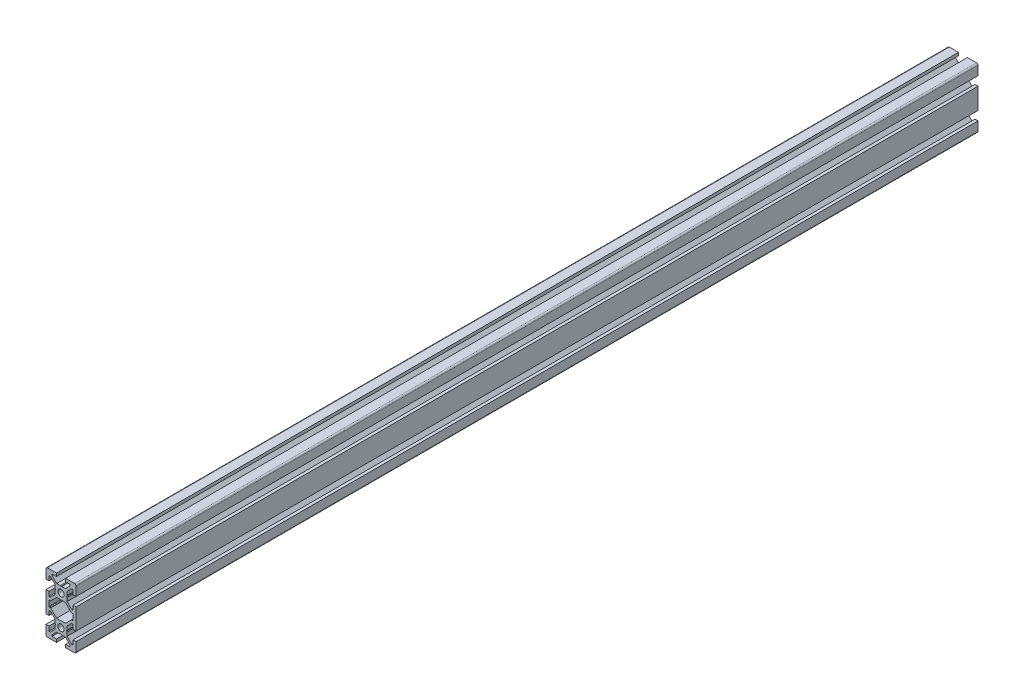
SolidWorks part; units mm, degrees
ref_plane "Front Plane" through (0, 0, 0) normal (0, 0, 1) x (1, 0, 0)
ref_plane "Top Plane" through (0, 0, 0) normal (0, 1, 0) x (1, 0, 0)
ref_plane "Right Plane" through (0, 0, 0) normal (1, 0, 0) x (0, 0, -1)
sketch "Sketch1" plane through (0, 0, 0) normal (0, 0, 1) x (1, 0, 0)
  line L0 (-8, -16) -> (-8, -13)
  line L1 (-8, -13) -> (-10, -13)
  line L2 (-10, -13) -> (-10, -19)
  line L3 (-9, -20) -> (-3, -20)
  line L4 (-3, -20) -> (-3, -18)
  line L5 (-3, -18) -> (-6, -18)
  line L6 (-6, -18) -> (-6, -17.0607)
  line L7 (-6, -17.0607) -> (-2.9393, -14)
  line L8 (-2.9393, -14) -> (-0.5196, -14)
  line L9 (-0.5196, -14) -> (0, -13.7)
  line L10 (0, -13.7) -> (0.5196, -14)
  line L11 (0.5196, -14) -> (2.9393, -14)
  line L12 (2.9393, -14) -> (6, -17.0607)
  line L13 (6, -17.0607) -> (6, -18)
  line L14 (6, -18) -> (3, -18)
  line L15 (3, -18) -> (3, -20)
  line L16 (3, -20) -> (9, -20)
  line L17 (10, -19) -> (10, -13)
  line L18 (10, -13) -> (8, -13)
  line L19 (8, -13) -> (8, -16)
  line L20 (8, -16) -> (7.0607, -16)
  line L21 (7.0607, -16) -> (4, -12.9393)
  line L22 (4, -12.9393) -> (4, -10.5196)
  line L23 (4, -10.5196) -> (3.7, -10)
  line L24 (3.7, -10) -> (4, -9.4804)
  line L25 (4, -9.4804) -> (4, -7.0607)
  line L26 (4, -7.0607) -> (7.0607, -4)
  line L27 (7.0607, -4) -> (8, -4)
  line L28 (8, -4) -> (8, -7)
  line L29 (8, -7) -> (10, -7)
  line L30 (10, -7) -> (10, 7)
  line L31 (10, 7) -> (8, 7)
  line L32 (8, 7) -> (8, 4)
  line L33 (8, 4) -> (7.0607, 4)
  line L34 (7.0607, 4) -> (4, 7.0607)
  line L35 (4, 7.0607) -> (4, 9.4804)
  line L36 (4, 9.4804) -> (3.7, 10)
  line L37 (3.7, 10) -> (4, 10.5196)
  line L38 (4, 10.5196) -> (4, 12.9393)
  line L39 (4, 12.9393) -> (7.0607, 16)
  line L40 (7.0607, 16) -> (8, 16)
  line L41 (8, 16) -> (8, 13)
  line L42 (8, 13) -> (10, 13)
  line L43 (10, 13) -> (10, 19)
  line L44 (9, 20) -> (3, 20)
  line L45 (3, 20) -> (3, 18)
  line L46 (3, 18) -> (6, 18)
  line L47 (6, 18) -> (6, 17.0607)
  line L48 (6, 17.0607) -> (2.9393, 14)
  line L49 (2.9393, 14) -> (0.5196, 14)
  line L50 (0.5196, 14) -> (0, 13.7)
  line L51 (0, 13.7) -> (-0.5196, 14)
  line L52 (-0.5196, 14) -> (-2.9393, 14)
  line L53 (-2.9393, 14) -> (-6, 17.0607)
  line L54 (-6, 17.0607) -> (-6, 18)
  line L55 (-6, 18) -> (-3, 18)
  line L56 (-3, 18) -> (-3, 20)
  line L57 (-3, 20) -> (-9, 20)
  line L58 (-10, 19) -> (-10, 13)
  line L59 (-10, 13) -> (-8, 13)
  line L60 (-8, 13) -> (-8, 16)
  line L61 (-8, 16) -> (-7.0607, 16)
  line L62 (-7.0607, 16) -> (-4, 12.9393)
  line L63 (-4, 12.9393) -> (-4, 10.5196)
  line L64 (-4, 10.5196) -> (-3.7, 10)
  line L65 (-3.7, 10) -> (-4, 9.4804)
  line L66 (-4, 9.4804) -> (-4, 7.0607)
  line L67 (-4, 7.0607) -> (-7.0607, 4)
  line L68 (-7.0607, 4) -> (-8, 4)
  line L69 (-8, 4) -> (-8, 7)
  line L70 (-8, 7) -> (-10, 7)
  line L71 (-10, 7) -> (-10, -7)
  line L72 (-10, -7) -> (-8, -7)
  line L73 (-8, -7) -> (-8, -4)
  line L74 (-8, -4) -> (-7.0607, -4)
  line L75 (-7.0607, -4) -> (-4, -7.0607)
  line L76 (-4, -7.0607) -> (-4, -9.4804)
  line L77 (-4, -9.4804) -> (-3.7, -10)
  line L78 (-3.7, -10) -> (-4, -10.5196)
  line L79 (-4, -10.5196) -> (-4, -12.9393)
  line L80 (-4, -12.9393) -> (-7.0607, -16)
  line L81 (-7.0607, -16) -> (-8, -16)
  line L82 (-7.0636, -2) -> (-7.7, -2)
  line L83 (-8, -1.7) -> (-8, 1.7)
  line L84 (-7.7, 2) -> (-7.0636, 2)
  line L85 (-6.8515, 2.0879) -> (-2.9393, 6)
  line L86 (-2.9393, 6) -> (2.9393, 6)
  line L87 (2.9393, 6) -> (6.8515, 2.0879)
  line L88 (7.0636, 2) -> (7.7, 2)
  line L89 (8, 1.7) -> (8, -1.7)
  line L90 (7.7, -2) -> (7.0636, -2)
  line L91 (6.8515, -2.0879) -> (2.9393, -6)
  line L92 (2.9393, -6) -> (-2.9393, -6)
  line L93 (-2.9393, -6) -> (-6.8515, -2.0879)
  circle A0 centre (0, -10) radius 2.1
  arc A1 (-10, -19) -> (-9, -20) centre (-9, -19) ccw
  arc A2 (9, -20) -> (10, -19) centre (9, -19) ccw
  arc A3 (10, 19) -> (9, 20) centre (9, 19) ccw
  arc A4 (-9, 20) -> (-10, 19) centre (-9, 19) ccw
  arc A5 (-7.7, -2) -> (-8, -1.7) centre (-7.7, -1.7) cw
  arc A6 (-8, 1.7) -> (-7.7, 2) centre (-7.7, 1.7) cw
  arc A7 (-7.0636, 2) -> (-6.8515, 2.0879) centre (-7.0636, 2.3) ccw
  arc A8 (6.8515, 2.0879) -> (7.0636, 2) centre (7.0636, 2.3) ccw
  arc A9 (7.7, 2) -> (8, 1.7) centre (7.7, 1.7) cw
  arc A10 (8, -1.7) -> (7.7, -2) centre (7.7, -1.7) cw
  arc A11 (7.0636, -2) -> (6.8515, -2.0879) centre (7.0636, -2.3) ccw
  arc A12 (-6.8515, -2.0879) -> (-7.0636, -2) centre (-7.0636, -2.3) ccw
  circle A13 centre (0, 10) radius 2.1
extrude "Boss-Extrude1" add sketch "Sketch1" against normal blind 600
